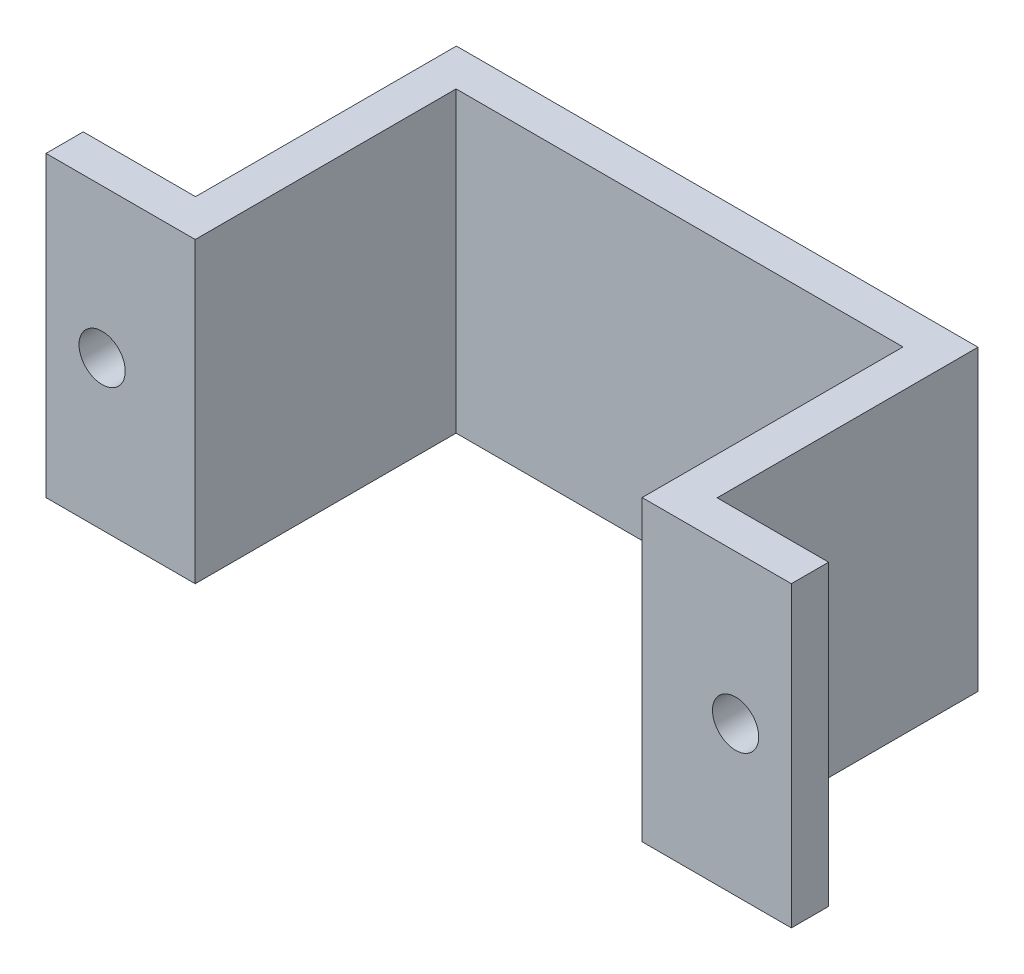
SolidWorks part; units mm, degrees
material "1060 Alloy"
ref_plane "Front Plane" through (0, 0, 0) normal (0, 0, 1) x (1, 0, 0)
ref_plane "Top Plane" through (0, 0, 0) normal (0, 1, 0) x (1, 0, 0)
ref_plane "Right Plane" through (0, 0, 0) normal (1, 0, 0) x (0, 0, -1)
sketch "Sketch1" plane through (0, 0, 0) normal (0, 0, 1) x (1, 0, 0)
  line L1 (63.5, -25.4) -> (-63.5, -25.4)
  line L2 (63.5, -25.4) -> (63.5, 25.4)
  line L3 (63.5, 25.4) -> (-63.5, 25.4)
  line L4 (-63.5, -25.4) -> (-63.5, 25.4)
  line L5 (63.5, -25.4) -> (-63.5, 25.4) construction
  line L6 (63.5, 25.4) -> (-63.5, -25.4) construction
  point P0 (0, 0)
  dimension "D1" = 50.8
  dimension "D2" = 127
extrude "Boss-Extrude1" add sketch "Sketch1" along normal blind 50.8
sketch "Sketch2" plane through (0, 0, 0) normal (0, 0, -1) x (-1, 0, 0)
  line L0 (-63.5, 25.4) -> (-44.5039, 25.4)
  line L1 (-63.5, 25.4) -> (63.5, 25.4) construction
  line L2 (-44.5039, 25.4) -> (-44.5039, -25.4)
  line L3 (63.5, -25.4) -> (-63.5, -25.4) construction
  line L4 (-44.5039, -25.4) -> (-63.5, -25.4)
  line L5 (-63.5, -25.4) -> (-63.5, 25.4)
  line L6 (63.5, 25.4) -> (44.3726, 25.4)
  line L7 (44.3726, 25.4) -> (44.3726, -25.4)
  line L8 (44.3726, -25.4) -> (63.5, -25.4)
  line L9 (63.5, -25.4) -> (63.5, 25.4)
  dimension "D1" = 44.5039
  dimension "D2" = 44.3726
extrude "Cut-Extrude1" cut sketch "Sketch2" against normal blind 44.45
sketch "Sketch3" plane through (0, 0, 50.8) normal (0, 0, 1) x (1, 0, 0)
  line L0 (63.5, 25.4) -> (-63.5, 25.4) construction
  line L1 (38.0757, -25.4) -> (-38.0757, -25.4)
  line L2 (38.0757, -25.4) -> (38.0757, 25.4)
  line L3 (38.0757, 25.4) -> (-38.0757, 25.4)
  line L4 (-38.0757, -25.4) -> (-38.0757, 25.4)
  line L5 (38.0757, -25.4) -> (-38.0757, 25.4) construction
  line L6 (38.0757, 25.4) -> (-38.0757, -25.4) construction
  point P0 (0, 0)
  dimension "D1" = 76.1513
extrude "Cut-Extrude2" cut sketch "Sketch3" against normal blind 44.45
sketch "Sketch5" plane through (0, 0, 44.45) normal (0, 0, -1) x (-1, 0, 0)
  line L0 (0, 0) -> (-80.6006, 0) construction
  line L1 (-54.0019, 25.4) -> (-54.0019, -25.4) construction
  line L2 (-44.5039, 25.4) -> (-63.5, 25.4) construction
  line L3 (-63.5, -25.4) -> (-44.5039, -25.4) construction
  circle A0 centre (-54.0019, 0) radius 3.937
  dimension "D1" = 7.874
  dimension "D2" = 54.0019
sketch "Sketch6" plane through (0, 0, 44.45) normal (0, 0, -1) x (-1, 0, 0)
  line L0 (0, 0) -> (75.8811, 0) construction
  line L1 (53.9363, 25.4) -> (53.9363, -25.4) construction
  line L2 (63.5, 25.4) -> (44.3726, 25.4) construction
  line L3 (44.3726, -25.4) -> (63.5, -25.4) construction
  circle A0 centre (53.9363, 0) radius 3.937
  dimension "D1" = 7.874
extrude "Cut-Extrude4" cut sketch "Sketch5" against normal blind 44.45
extrude "Cut-Extrude5" cut sketch "Sketch6" against normal blind 44.45
